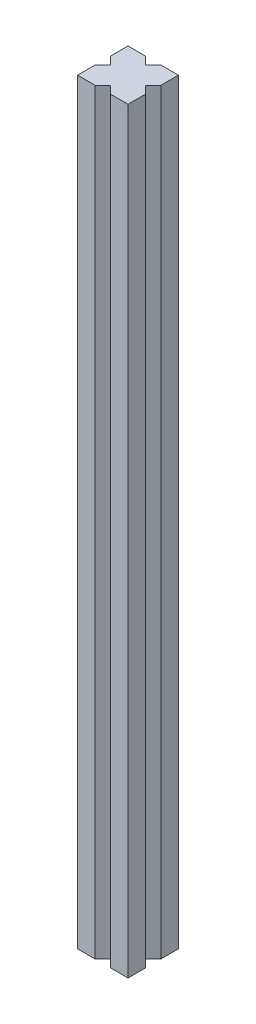
SolidWorks part; units mm, degrees
ref_plane "Front" through (0, 0, 0) normal (0, 0, 1) x (1, 0, 0)
ref_plane "Top" through (0, 0, 0) normal (0, 1, 0) x (1, 0, 0)
ref_plane "Right" through (0, 0, 0) normal (1, 0, 0) x (0, 0, -1)
sketch "Skizze1" plane through (0, 0, 0) normal (0, 1, 0) x (1, 0, 0)
  line L1 (0, 0) -> (20, 0)
  line L2 (0, 0) -> (0, 20)
  line L3 (0, 20) -> (20, 20)
  line L4 (20, 0) -> (20, 20)
  dimension "D1" = 20
extrude "Aufsatz-Linear austragen1" add sketch "Skizze1" along normal blind 300
sketch "Skizze2" plane through (0, 300, 0) normal (0, 1, 0) x (1, 0, 0)
  line L0 (10, 20) -> (10, 0) construction
  line L1 (20, 20) -> (0, 20) construction
  line L2 (0, 0) -> (20, 0) construction
  line L3 (0, 10) -> (20, 10) construction
  line L4 (0, 20) -> (0, 0) construction
  line L5 (20, 0) -> (20, 20) construction
  line L6 (7, 20) -> (10, 17)
  line L7 (13, 20) -> (10, 17)
  line L8 (10, 10) -> (20, 20) construction
  line L9 (7, 20) -> (13, 20)
  line L10 (20, 13) -> (17, 10)
  line L11 (20, 7) -> (17, 10)
  line L12 (20, 7) -> (20, 13)
  line L13 (0, 7) -> (0, 13)
  line L14 (0, 7) -> (3, 10)
  line L15 (0, 13) -> (3, 10)
  line L16 (7, 0) -> (13, 0)
  line L17 (13, 0) -> (10, 3)
  line L18 (7, 0) -> (10, 3)
  dimension "D1" = 3
  dimension "D2" = 3
extrude "Schnitt-Linear austragen1" cut sketch "Skizze2" against normal through all
